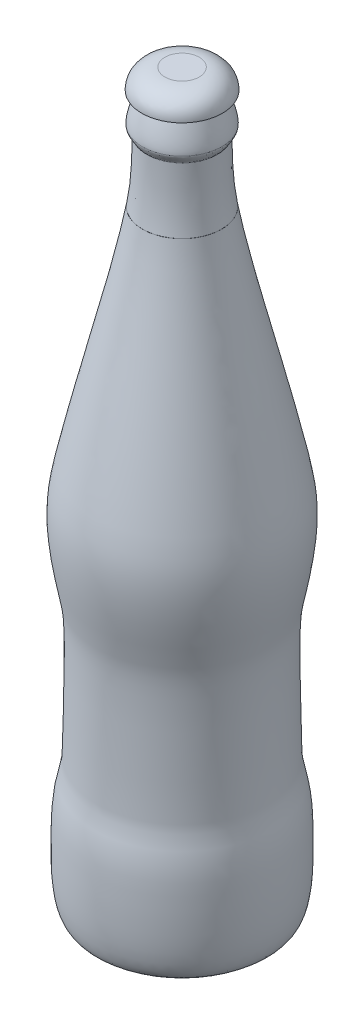
SolidWorks part; units mm, degrees
ref_plane "Plano frontal" through (0, 0, 0) normal (0, 0, 1) x (1, 0, 0)
ref_plane "Plano superior" through (0, 0, 0) normal (0, 1, 0) x (1, 0, 0)
ref_plane "Plano direito" through (0, 0, 0) normal (1, 0, 0) x (0, 0, -1)
sketch "Esboço1" plane through (0, 0, 0) normal (0, 0, 1) x (1, 0, 0)
  line L0 (46.2661, 215.0263) -> (246.2661, 215.0263) construction
  line L1 (103.0084, 498.8129) -> (276.3418, 498.8129) construction
  line L2 (113.9574, 392.5843) -> (647.2908, 392.5843) construction
  line L3 (142.8895, 341.4746) -> (372.2229, 341.4746) construction
sketch "Esboço2" plane through (0, 0, 0) normal (0, 0, 1) x (1, 0, 0)
  line L0 (0, 0) -> (0, 80) construction
  line L1 (-10, 80) -> (10, 80)
  line L2 (-10, 80) -> (-10, 0)
  line L3 (-10, 0) -> (10, 0)
  line L4 (10, 80) -> (10, 0)
  dimension "D1" = 20
  dimension "D2" = 80
sketch "Esboço3" plane through (0, 0, 0) normal (0, 0, 1) x (1, 0, 0)
  line L0 (91.9576, 2.2294) -> (92.4036, 2.2294) construction
  line L7 (96.4628, 74.8712) -> (100.7001, 74.8712) construction
  line L9 (96.4124, 77.9723) -> (100.7001, 77.9723) construction
  line L10 (96.9395, 76.0156) -> (96.9395, 71.7901) construction
  line L11 (96.4628, 74.3714) -> (96.4628, 75.3709) construction
  line L12 (96.4628, 76.1408) -> (96.4628, 73.6003) construction
  line L13 (99.7788, 80.0892) -> (101.7689, 80.0892) construction
  line L14 (96.4124, 77.3076) -> (96.4124, 78.5598) construction
  line L15 (98.8726, 80.0892) -> (100.7001, 80.0892)
  line L18 (100.7001, 42.5631) -> (100.7001, -6.3358) construction
  line L20 (96.4124, 77.9723) -> (97.3026, 77.9723)
  line L22 (92.1806, 2.2294) -> (100.7001, 2.2294)
  line L23 (100.7001, 2.2294) -> (100.7001, 80.0892)
  line L24 (91.1519, 33.379) -> (110.2483, 33.379) construction
  line L25 (100.7001, 33.379) -> (100.7001, 88.6869) construction
  line L26 (96.9395, 73.9029) -> (101.3736, 73.9029) construction
  line L27 (90.8345, 10.5453) -> (101.8776, 10.5453) construction
  spline S0 degree 3 poles (92.1806, 2.2294) (90.783, 2.2294) (90.7514, 8.991) (90.9536, 13.277) (91.6726, 15.7438) (91.6973, 20.0334) (92.0135, 28.6827) (91.0575, 33.7416) (90.0503, 38.648) (92.5926, 50.7126) (95.2451, 60.4385) (96.7988, 68.7214) (96.9395, 71.1682) (96.9395, 73.9029) knots 0 0 0 0 0.088023 0.127395 0.153536 0.168258 0.262799 0.291491 0.426488 0.485596 0.823469 0.879133 1 1 1 1
  spline S5 degree 3 poles (96.4628, 74.8712) (96.4628, 74.56) (96.9395, 74.0301) (96.9395, 73.9029) knots 0 0 0 0 1 1 1 1
  spline S6 degree 2 poles (96.4628, 74.8712) (96.4628, 75.6979) (97.3026, 77.9723) knots 0 0 0 1 1 1
  spline S7 degree 3 poles (98.8726, 80.0892) (97.6184, 80.0892) (96.4124, 79.3528) (96.4124, 77.9723) knots 0 0 0 0 1 1 1 1
revolve "Revolução1" add sketch "Esboço3" angle 360 about L23
sketch "Esboço4" plane through (0, 2.2294, 0) normal (0, -1, 0) x (1, 0, 0)
  circle A0 centre (100.7001, 0) radius 0.5
  dimension "D1" = 1
extrude "Corte-extrusão1" cut sketch "Esboço4" against normal blind 0.4
ref_plane "Plano1" through (0, 67.2294, 0) normal (0, -1, 0) x (-1, 0, 0)
sketch "Esboço5" plane through (0, 67.2294, 0) normal (0, -1, 0) x (-1, 0, 0)
  circle A0 centre (-100.7001, 0) radius 12.5749
extrude "Corte-extrusão2" cut sketch "Esboço5" against normal blind 0.01
